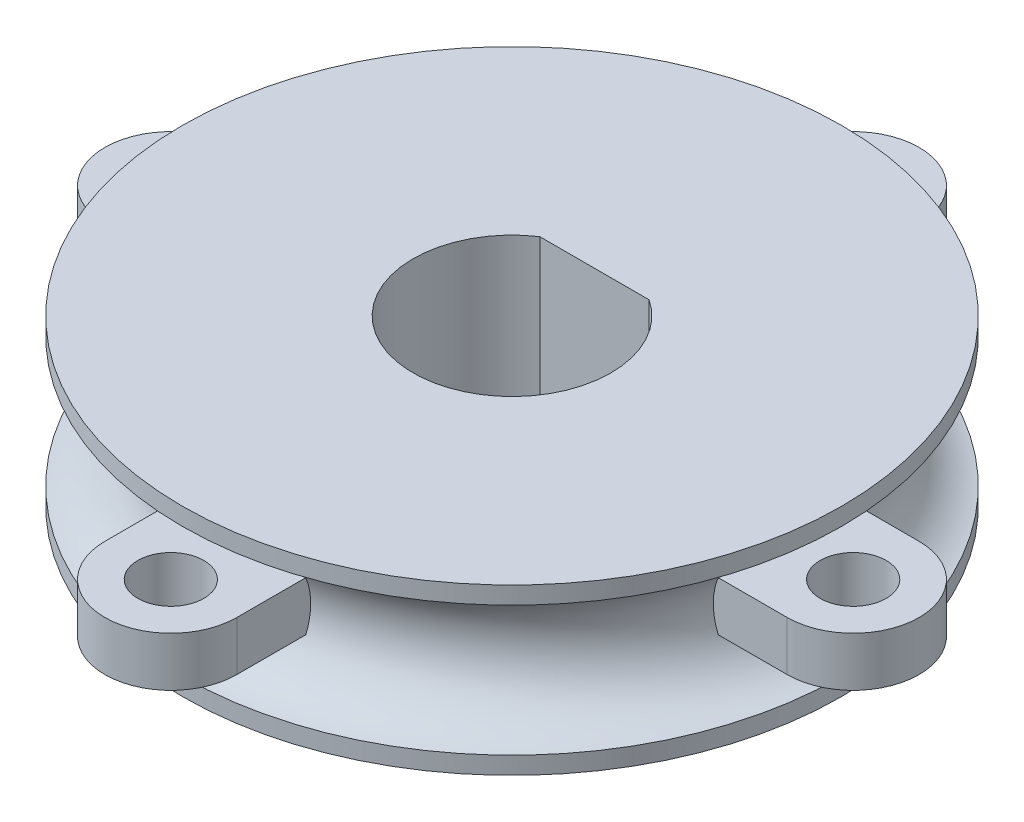
SolidWorks part; units mm, degrees
ref_plane "Front Plane" through (0, 0, 0) normal (0, 0, 1) x (1, 0, 0)
ref_plane "Top Plane" through (0, 0, 0) normal (0, 1, 0) x (1, 0, 0)
ref_plane "Right Plane" through (0, 0, 0) normal (1, 0, 0) x (0, 0, -1)
sketch "Sketch2" plane through (0, 0, 0) normal (0, 0, 1) x (1, 0, 0)
  line L0 (0, 0) -> (0, 9.4259) construction
  line L1 (0, 2.5) -> (0, -2.5)
  line L2 (0, -2.5) -> (10, -2.5)
  line L3 (10, -2.5) -> (10, -1.9696)
  line L4 (10, 1.9696) -> (10, 2.5)
  line L5 (10, 2.5) -> (0, 2.5)
  line L6 (10, -1.9696) -> (10.3473, 0) construction
  line L7 (10.3473, 0) -> (10, 1.9696) construction
  arc A1 (10, 1.9696) -> (10, -1.9696) centre (10.3473, 0) ccw
  point P9 (0, 0)
  dimension "D1" = 2
  dimension "D2" = 20
  dimension "D3" = 5
  dimension "D4" = 160
revolve "Revolve1" add sketch "Sketch2" angle 360 about L0
sketch "Sketch3" plane through (0, 2.5, 0) normal (0, 1, 0) x (1, 0, 0)
  line L0 (-1.6583, 2.5) -> (1.6583, 2.5)
  arc A0 (-1.6583, 2.5) -> (1.6583, 2.5) centre (0, 0) ccw
  point P1 (0, -3)
  dimension "D1" = 3
  dimension "D2" = 5.5
extrude "Cut-Extrude1" cut sketch "Sketch3" against normal through all
sketch "Sketch4" plane through (0, 0, 0) normal (0, 1, 0) x (1, 0, 0)
  line L0 (5.3473, 2) -> (10.3473, 2)
  line L1 (10.3473, -2) -> (5.3473, -2)
  line L2 (5.3473, -2) -> (5.3473, 2)
  line L3 (10.3473, 0) -> (8.3473, 0) construction
  circle A2 centre (10.3473, 0) radius 1
  arc A3 (10.3473, 2) -> (10.3473, -2) centre (10.3473, 0) cw
  point P8 (10.3473, 0)
  dimension "D1" = 2
  dimension "D2" = 2
  dimension "D3" = 5
  dimension "D4" = 2
extrude "Boss-Extrude1" add sketch "Sketch4" along normal mid plane 1.5
pattern_circular "CirPattern1" count 4 over 360 about axis through (0, 0, 0) along (0, 1, 0) of "Boss-Extrude1"
